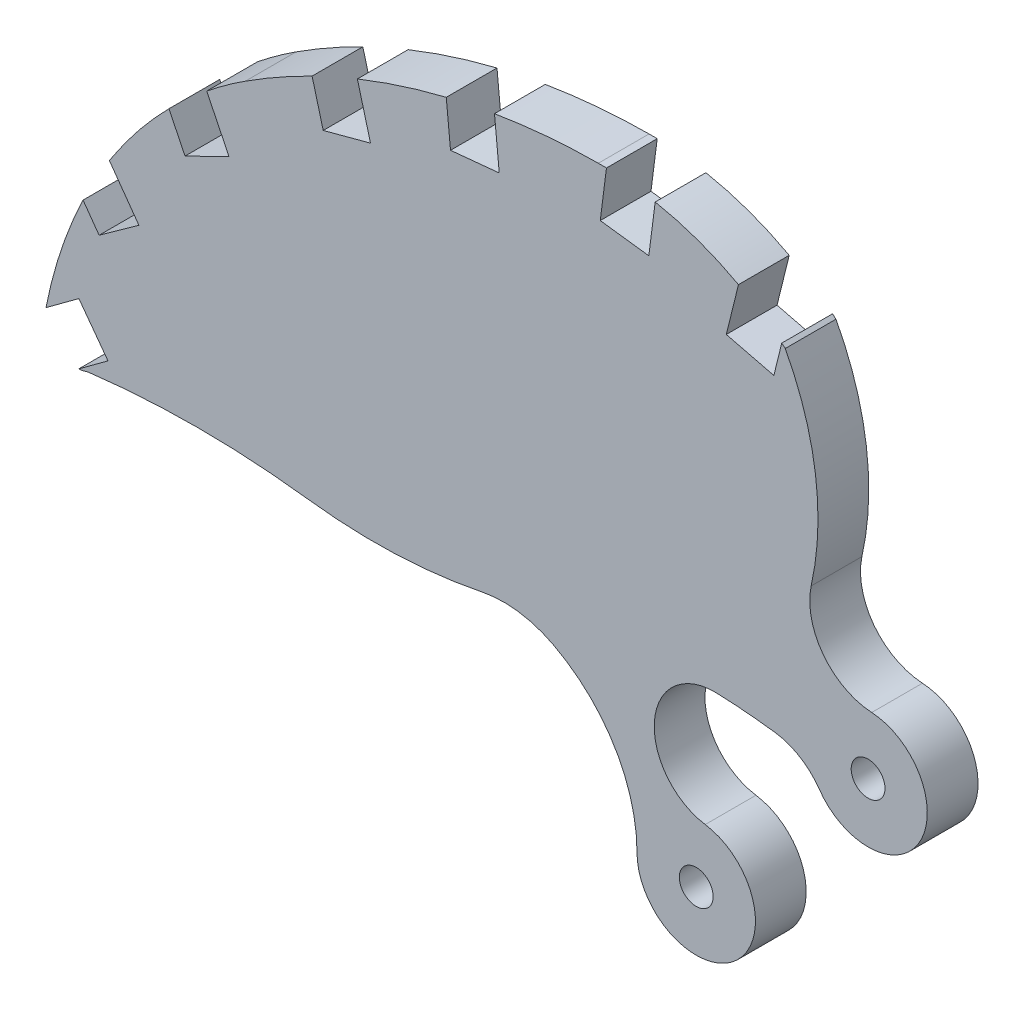
SolidWorks part; units mm, degrees
material "Acrylic (Medium-high impact)"
ref_plane "Front Plane" through (0, 0, 0) normal (0, 0, 1) x (1, 0, 0)
ref_plane "Top Plane" through (0, 0, 0) normal (0, 1, 0) x (1, 0, 0)
ref_plane "Right Plane" through (0, 0, 0) normal (1, 0, 0) x (0, 0, -1)
sketch "스케치1" plane through (0, 0, 0) normal (0, 0, 1) x (1, 0, 0)
  line L0 (7.4307, -0.7322) -> (6.755, -2.1133) construction
  line L1 (6.755, -2.1133) -> (6.7364, -3.6508) construction
  line L2 (0.5319, -10.0867) -> (0, -10.0461) construction
  line L3 (0, -10.0461) -> (-0.5319, -10.0867) construction
  line L4 (0, -10.0461) -> (0, 0) construction
  line L5 (7.4307, -0.7322) -> (-7.4307, -0.7322) construction
  line L6 (7.4307, -0.7322) -> (6.7364, -3.6508) construction
  line L7 (7.4307, -0.7322) -> (-48.1678, 12.494) construction
  line L8 (6.7364, -3.6508) -> (-48.862, 9.5754) construction
  line L9 (-48.1678, 12.494) -> (-48.862, 9.5754) construction
  line L10 (-0.9163, -1.8303) -> (-48.862, 9.5754) construction
  line L11 (-0.9163, -1.8303) -> (0, 0) construction
  line L12 (0, 0) -> (0.2331, 0.98) construction
  line L13 (0.2331, 0.98) -> (-10.0443, 3.4249) construction
  arc A0 (-7.4307, -0.7322) -> (7.4307, -0.7322) centre (0, -38.0708) cw construction
  arc A1 (-6.7364, -3.6508) -> (6.7364, -3.6508) centre (0, -38.0708) cw construction
  circle A2 centre (-10.16, -2.9233) radius 3.5 construction
  circle A3 centre (10.16, -2.9233) radius 3.5 construction
  arc A4 (-10.16, -2.9233) -> (10.16, -2.9233) centre (0, -38.0708) cw construction
  circle A5 centre (-10.16, -2.9233) radius 1 construction
  circle A6 centre (10.16, -2.9233) radius 1
  circle A7 centre (0, -13.5461) radius 3.5 construction
  circle A8 centre (0, -13.5461) radius 1
  arc A9 (0.5319, -10.0867) -> (1.1932, -3.0181) centre (1.0723, -6.572) cw
  arc A10 (-1.1932, -3.0181) -> (-0.5319, -10.0867) centre (-1.0723, -6.572) cw construction
  arc A11 (-6.7364, -3.6508) -> (-1.1932, -3.0181) centre (0, -38.0708) cw construction
  arc A12 (1.1932, -3.0181) -> (6.7364, -3.6508) centre (0, -38.0708) cw
  arc A13 (7.4307, -0.7322) -> (6.7364, -3.6508) centre (10.16, -2.9233) cw construction
  arc A14 (0.5319, -10.0867) -> (-0.5319, -10.0867) centre (0, -13.5461) cw construction
  arc A16 (-7.0816, -4.5886) -> (-0.9163, -1.8303) centre (-2.2006, -7.229) ccw construction
  arc A17 (-7.0816, -4.5886) -> (-6.7364, -3.6508) centre (-10.16, -2.9233) ccw construction
  arc A18 (-10.0443, 3.4249) -> (7.4307, -0.7322) centre (-5.22, -15.1036) cw construction
  arc A19 (10.3737, 0.5701) -> (6.7929, 5.259) centre (10.6118, 4.4637) cw
  arc A20 (6.7929, 5.259) -> (-5.7878, 20.6104) centre (-5.6912, 7.8589) ccw construction
  arc A21 (-5.7878, 20.6104) -> (-26.6538, 14.3799) centre (-5.492, -18.4355) ccw
  arc A22 (-26.6538, 14.3799) -> (-34.4856, 6.6112) centre (-12.2185, -8.0048) ccw
  arc A23 (-3.5, -13.5461) -> (-11.2117, -4.4479) centre (-12.7228, -13.5461) ccw
  arc A24 (-34.4856, 6.6112) -> (-38.4363, -3.0897) centre (-11.7888, -8.2868) ccw
  arc A25 (-38.4363, -3.0897) -> (-35.9789, -5.1654) centre (-36.6287, -3.4423) ccw
  arc A26 (-35.9789, -5.1654) -> (-22.9613, -5.1705) centre (-29.4906, -57.4047) cw
  arc A27 (-22.9613, -5.1705) -> (-11.2117, -4.4479) centre (-19.0089, 26.4482) ccw
  arc A28 (-3.5, -13.5461) -> (0.5319, -10.0867) centre (0, -13.5461) ccw
  arc A29 (6.7364, -3.6508) -> (10.3737, 0.5701) centre (10.16, -2.9233) ccw
  arc A30 (-5.7878, 20.6104) -> (5.2627, 16.6512) centre (-5.6222, 3.6717) cw
  arc A31 (5.2627, 16.6512) -> (6.7929, 5.259) centre (-9.2975, 8.8967) cw
  dimension "D1" = 2.5
  dimension "D2" = 2
  dimension "D4" = 3.556
  dimension "D7" = 57.15
  dimension "D5" = 20.32
  dimension "D6" = 3
extrude "보스-돌출1" add sketch "스케치1" along normal blind 3
sketch "스케치3" plane through (0, 0, 3) normal (0, 0, 1) x (1, 0, 0)
  line L0 (-37.1885, -5.7839) -> (-34.7755, -4.0014)
  line L1 (-37.1885, -5.7839) -> (-38.9086, -3.4553)
  line L2 (-34.7755, -4.0014) -> (-36.4956, -1.6728)
  line L3 (-38.9086, -3.4553) -> (-36.4956, -1.6728)
  line L4 (-37.1885, -5.7839) -> (-36.4956, -1.6728) construction
  line L5 (-34.7755, -4.0014) -> (-38.9086, -3.4553) construction
  line L6 (-35.3003, 2.1683) -> (-32.9459, 3.8528)
  line L7 (-35.3003, 2.1683) -> (-37.046, 4.6081)
  line L8 (-32.9459, 3.8528) -> (-34.6916, 6.2926)
  line L9 (-37.046, 4.6081) -> (-34.6916, 6.2926)
  line L10 (-35.3003, 2.1683) -> (-34.6916, 6.2926) construction
  line L11 (-32.9459, 3.8528) -> (-37.046, 4.6081) construction
  line L12 (-30.2198, 8.761) -> (-27.6198, 10.0342)
  line L13 (-30.2198, 8.761) -> (-31.5392, 11.4553)
  line L14 (-27.6198, 10.0342) -> (-28.9392, 12.7285)
  line L15 (-31.5392, 11.4553) -> (-28.9392, 12.7285)
  line L16 (-30.2198, 8.761) -> (-28.9392, 12.7285) construction
  line L17 (-27.6198, 10.0342) -> (-31.5392, 11.4553) construction
  line L18 (-22.052, 14.156) -> (-19.2557, 14.9055)
  line L19 (-22.052, 14.156) -> (-22.8288, 17.0536)
  line L20 (-19.2557, 14.9055) -> (-20.0325, 17.8032)
  line L21 (-22.8288, 17.0536) -> (-20.0325, 17.8032)
  line L22 (-22.052, 14.156) -> (-20.0325, 17.8032) construction
  line L23 (-19.2557, 14.9055) -> (-22.8288, 17.0536) construction
  line L24 (-11.0031, -4.3945) -> (-13.2384, 18.6112) construction
  line L25 (-15.3627, -5.2073) -> (-21.0422, 15.9796) construction
  line L26 (-21.7218, -5.3009) -> (-30.0832, 11.7733) construction
  line L27 (-29.3203, -3.7021) -> (-35.5007, 4.9359) construction
  line L28 (-7.2641, -6.1121) -> (-3.8515, 20.5771) construction
  line L29 (4.4511, 20.4162) -> (-3.5981, -12.2045) construction
  line L30 (-14.5268, 16.9035) -> (-11.6453, 17.1834)
  line L31 (-14.5268, 16.9035) -> (-14.8169, 19.8894)
  line L32 (-11.6453, 17.1834) -> (-11.9354, 20.1694)
  line L33 (-14.8169, 19.8894) -> (-11.9354, 20.1694)
  line L34 (-14.5268, 16.9035) -> (-11.9354, 20.1694) construction
  line L35 (-11.6453, 17.1834) -> (-14.8169, 19.8894) construction
  line L36 (-5.2942, 20.7072) -> (-2.4225, 20.34)
  line L37 (-5.2942, 20.7072) -> (-5.6747, 17.7314)
  line L38 (-2.4225, 20.34) -> (-2.803, 17.3643)
  line L39 (-5.6747, 17.7314) -> (-2.803, 17.3643)
  line L40 (-5.2942, 20.7072) -> (-2.803, 17.3643) construction
  line L41 (-2.4225, 20.34) -> (-5.6747, 17.7314) construction
  line L42 (2.4969, 18.5387) -> (5.3076, 17.8452)
  line L43 (2.4969, 18.5387) -> (1.7782, 15.6261)
  line L44 (5.3076, 17.8452) -> (4.5889, 14.9325)
  line L45 (1.7782, 15.6261) -> (4.5889, 14.9325)
  line L46 (2.4969, 18.5387) -> (4.5889, 14.9325) construction
  line L47 (5.3076, 17.8452) -> (1.7782, 15.6261) construction
  line L48 (-38.11, -4.5365) -> (-33.4957, -1.128) construction
  line L49 (6.6317, 15.3675) -> (7.0045, 12.3907) construction
  line L50 (6.6317, 15.3675) -> (9.5191, 15.7291) construction
  line L51 (7.0045, 12.3907) -> (9.8919, 12.7524) construction
  line L52 (9.5191, 15.7291) -> (9.8919, 12.7524) construction
  line L53 (6.6317, 15.3675) -> (9.8919, 12.7524) construction
  line L54 (7.0045, 12.3907) -> (9.5191, 15.7291) construction
  line L55 (8.2618, 14.0599) -> (10.6038, -4.6391) construction
  arc A0 (-38.4363, -3.0897) -> (-35.9789, -5.1654) centre (-36.6287, -3.4423) ccw construction
  arc A1 (-22.9613, -5.1705) -> (-11.2117, -4.4479) centre (-19.0089, 26.4482) ccw construction
  arc A2 (-26.6538, 14.3799) -> (-34.4856, 6.6112) centre (-12.2185, -8.0048) ccw construction
  arc A3 (-34.4856, 6.6112) -> (-38.4363, -3.0897) centre (-11.7888, -8.2868) ccw construction
  arc A4 (-3.5, -13.5461) -> (-11.2117, -4.4479) centre (-12.7228, -13.5461) ccw construction
  arc A5 (-5.7878, 20.6104) -> (-26.6538, 14.3799) centre (-5.492, -18.4355) ccw construction
  arc A9 (5.2627, 16.6512) -> (-5.7878, 20.6104) centre (-5.6222, 3.6717) ccw construction
  arc A11 (6.7364, -3.6508) -> (1.1932, -3.0181) centre (0, -38.0708) ccw construction
  point P1 (-36.8421, -3.7284)
  point P5 (-34.9959, 4.2304)
  point P6 (-29.5795, 10.7447)
  point P21 (-21.0422, 15.9796)
  point P56 (3.5429, 16.7356)
  point P59 (-4.0486, 19.0357)
  point P64 (8.2618, 14.0599)
  point P70 (-13.2311, 18.5364)
  dimension "D1" = 2.895
  dimension "D2" = 3
  dimension "D3" = 3
  dimension "D4" = 3
  dimension "D5" = 3
  dimension "D6" = 2.91
  dimension "D7" = 2.895
  dimension "D8" = 2.895
  dimension "D9" = 2.895
  dimension "D10" = 2.895
  dimension "D11" = 2.895
  dimension "D12" = 2.895
  dimension "D13" = 3
  dimension "D14" = 3
  dimension "D15" = 3
  dimension "D16" = 3
extrude "컷-돌출1" cut sketch "스케치3" against normal up to surface (3 mm away) up to face at (-10.239, 0.8013, 0)
fillet "필렛1" radius 6.35 1 edges at (-11.2117, -4.4479, 1.5)
fillet "필렛2" radius 3.81 1 edges at (6.7364, -3.6508, 1.5)
